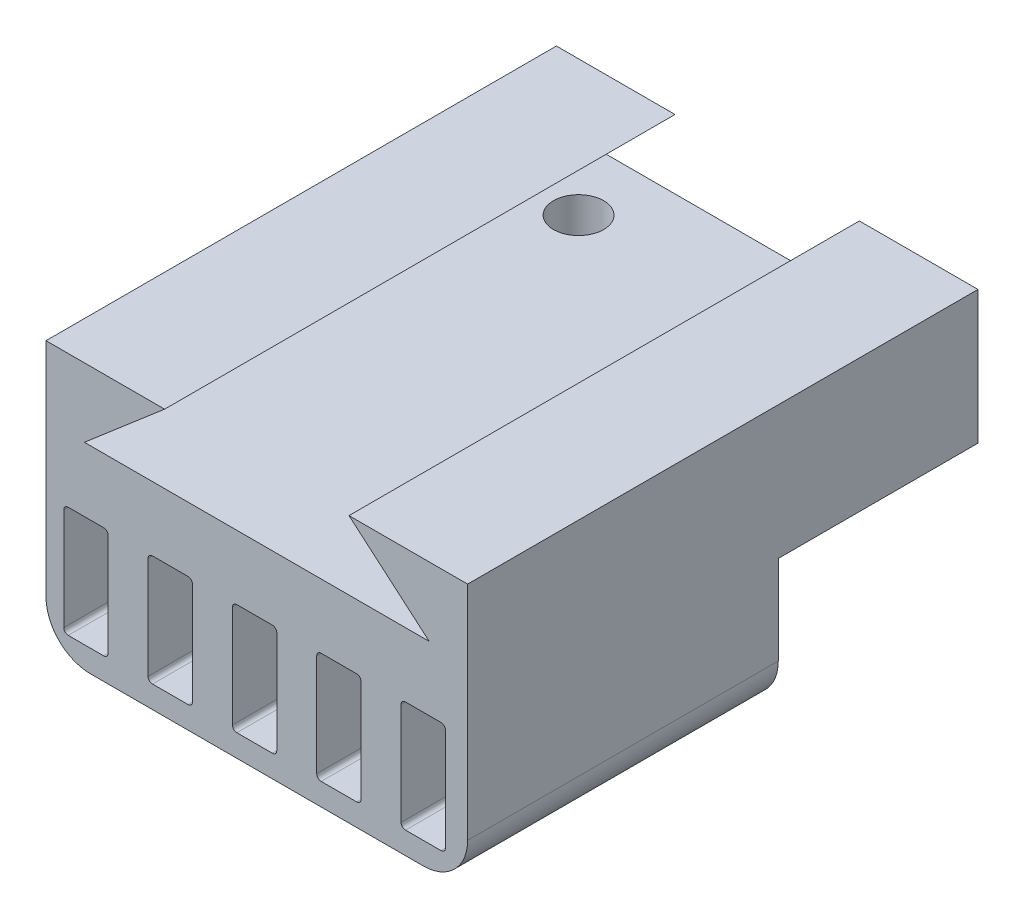
SolidWorks part; units mm, degrees
material "PLA"
ref_plane "Front" through (0, 0, 0) normal (0, 0, 1) x (1, 0, 0)
ref_plane "Top" through (0, 0, 0) normal (0, 1, 0) x (1, 0, 0)
ref_plane "Right" through (0, 0, 0) normal (1, 0, 0) x (0, 0, -1)
sketch "Sketch1" plane through (0, 0, 0) normal (0, 0, 1) x (1, 0, 0)
  line L0 (5.08, -21.59) -> (-5.08, -21.59)
  line L5 (-5.1627, -21.4936) -> (5.1627, -21.4936)
  line L6 (-5.1627, -21.4936) -> (-9.8683, -25.527)
  line L7 (-9.8683, -25.527) -> (9.8683, -25.527)
  line L8 (9.8683, -25.527) -> (5.1627, -21.4936)
  line L9 (-5.08, -21.59) -> (-5.2751, -21.59)
  line L10 (5.08, -21.59) -> (5.2751, -21.59)
  line L11 (-5.08, -21.59) -> (-5.2751, -21.59)
  line L12 (9.525, -21.59) -> (9.525, -17.6598)
  line L13 (5.08, -21.59) -> (9.525, -21.59)
  line L14 (9.525, -25.4) -> (5.08, -21.59)
  line L15 (-9.525, -25.4) -> (9.525, -25.4)
  line L16 (-5.08, -21.59) -> (-9.525, -25.4)
  line L17 (-9.525, -21.59) -> (-5.08, -21.59)
  line L18 (-9.525, -17.6598) -> (-9.525, -21.59)
  line L19 (9.525, -21.59) -> (9.525, -17.6598)
  line L20 (5.08, -21.59) -> (9.525, -21.59)
  line L21 (9.525, -25.4) -> (5.08, -21.59)
  line L22 (-9.525, -25.4) -> (9.525, -25.4)
  line L23 (-5.08, -21.59) -> (-9.525, -25.4)
  line L24 (-9.525, -21.59) -> (-5.08, -21.59)
  line L25 (-9.525, -17.6598) -> (-9.525, -21.59)
  line L27 (-12.065, -29.21) -> (12.065, -29.21)
  line L28 (-12.065, -29.21) -> (-12.065, -21.59)
  line L29 (-12.065, -21.59) -> (12.065, -21.59)
  line L30 (12.065, -29.21) -> (12.065, -21.59)
  arc A2 (-20.6375, -11.1054) -> (-19.2555, -10.6965) centre (-20.6375, -8.5654) ccw
  arc A3 (19.2555, -10.6965) -> (20.6375, -11.1054) centre (20.6375, -8.5654) ccw
  arc A4 (-20.6375, -11.1054) -> (-19.2555, -10.6965) centre (-20.6375, -8.5654) ccw
  arc A5 (19.2555, -10.6965) -> (20.6375, -11.1054) centre (20.6375, -8.5654) ccw
  ellipse E2 centre (0, 0) end of major axis (25.4, 0) minor radius 19.05 (-20.6375, -11.1054) -> (-9.525, -17.6598) ccw
  ellipse E3 centre (0, 0) end of major axis (25.4, 0) minor radius 19.05 (9.525, -17.6598) -> (20.6375, -11.1054) ccw
  ellipse E4 centre (0, 0) end of major axis (25.4, 0) minor radius 19.05 (-20.6375, -11.1054) -> (-9.525, -17.6598) ccw
  ellipse E5 centre (0, 0) end of major axis (25.4, 0) minor radius 19.05 (9.525, -17.6598) -> (20.6375, -11.1054) ccw
  spline S1 degree 3 poles (-2166.445, -15849.0793) (-418.6607, -134.144) (57.4604, 23.5329) (18.4102, -11.4784) (18.1685, -11.6861) (17.4022, -12.3125) (16.8339, -12.7373) (15.8949, -13.3659) (15.5674, -13.5742) (14.8823, -13.9857) (14.5239, -14.1894) (13.7828, -14.586) (13.3995, -14.7793) (12.6066, -15.1542) (12.1964, -15.336) (11.3542, -15.6842) (10.9219, -15.8506) (10.0343, -16.1671) (9.5775, -16.3175) (8.1859, -16.7374) (7.2281, -16.9768) (5.7448, -17.2706) (5.2427, -17.3576) (4.2222, -17.5087) (3.7022, -17.5728) (2.6581, -17.6756) (2.1332, -17.7144) (1.0777, -17.7665) (0.5456, -17.7797) (-1.0381, -17.7806) (-2.0822, -17.7301) (-3.6313, -17.5808) (-4.1449, -17.5187) (-5.1662, -17.3701) (-5.6756, -17.2832) (-6.6756, -17.0872) (-7.1675, -16.9781) (-8.1355, -16.7387) (-8.6125, -16.608) (-9.5437, -16.3283) (-9.9984, -16.1792) (-10.887, -15.8637) (-11.3215, -15.697) (-12.5878, -15.1754) (-13.3817, -14.7994) (-14.8691, -14.0059) (-15.5563, -13.5917) (-16.8227, -12.7456) (-17.3958, -12.3175) (-61.9722, 24.1081) (359.4859, -21.3348) (4215.4566, -15431.1683) knots -5.38 -5.38 -5.38 -5.38 0.03125 0.03125 0.0625 0.0625 0.125 0.125 0.15625 0.15625 0.1875 0.1875 0.21875 0.21875 0.25 0.25 0.28125 0.28125 0.3125 0.3125 0.375 0.375 0.40625 0.40625 0.4375 0.4375 0.46875 0.46875 0.5 0.5 0.5625 0.5625 0.59375 0.59375 0.625 0.625 0.65625 0.65625 0.6875 0.6875 0.71875 0.71875 0.75 0.75 0.8125 0.8125 0.875 0.875 0.9375 0.9375 6.300617 6.300617 6.300617 6.300617 only from (19.2555, -10.6965) to (-19.2555, -10.6965)
  spline S2 degree 3 poles (19.2555, -10.6965) (19.0657, -10.8817) (18.8587, -11.0763) (18.4102, -11.4784) (18.1685, -11.6861) (17.4022, -12.3125) (16.8339, -12.7373) (15.8949, -13.3659) (15.5674, -13.5742) (14.8823, -13.9857) (14.5239, -14.1894) (13.7828, -14.586) (13.3995, -14.7793) (12.6066, -15.1542) (12.1964, -15.336) (11.3542, -15.6842) (10.9219, -15.8506) (10.0343, -16.1671) (9.5775, -16.3175) (8.1859, -16.7374) (7.2281, -16.9768) (5.7448, -17.2706) (5.2427, -17.3576) (4.2222, -17.5087) (3.7022, -17.5728) (2.6581, -17.6756) (2.1332, -17.7144) (1.0777, -17.7665) (0.5456, -17.7797) (-1.0381, -17.7806) (-2.0822, -17.7301) (-3.6313, -17.5808) (-4.1449, -17.5187) (-5.1662, -17.3701) (-5.6756, -17.2832) (-6.6756, -17.0872) (-7.1675, -16.9781) (-8.1355, -16.7387) (-8.6125, -16.608) (-9.5437, -16.3283) (-9.9984, -16.1792) (-10.887, -15.8637) (-11.3215, -15.697) (-12.5878, -15.1754) (-13.3817, -14.7994) (-14.8691, -14.0059) (-15.5563, -13.5917) (-16.8227, -12.7456) (-17.3958, -12.3175) (-18.4228, -11.4783) (-18.8731, -11.0698) (-19.2555, -10.6965) knots 0 0 0 0 0.03125 0.03125 0.0625 0.0625 0.125 0.125 0.15625 0.15625 0.1875 0.1875 0.21875 0.21875 0.25 0.25 0.28125 0.28125 0.3125 0.3125 0.375 0.375 0.40625 0.40625 0.4375 0.4375 0.46875 0.46875 0.5 0.5 0.5625 0.5625 0.59375 0.59375 0.625 0.625 0.65625 0.65625 0.6875 0.6875 0.71875 0.71875 0.75 0.75 0.8125 0.8125 0.875 0.875 0.9375 0.9375 1 1 1 1
  dimension "D1" = 0
  dimension "D2" = 2.54
  dimension "D3" = 2.54
  dimension "D4" = 7.62
  dimension "D5" = 0.127
extrude "Boss-Extrude2" add sketch "Sketch1" along normal blind 25.4 contours L27 L30 L29 L20 L8 L7 L6 L24 L28
sketch "Sketch3" plane through (0, -29.21, 0) normal (0, -1, 0) x (-1, 0, 0)
  line L0 (12.065, -25.4) -> (12.065, 0) construction
  line L1 (-12.065, -25.4) -> (12.065, -25.4)
  line L2 (-12.065, -25.4) -> (-12.065, -7.62)
  line L3 (-12.065, -7.62) -> (12.065, -7.62)
  line L4 (12.065, -25.4) -> (12.065, -7.62)
  dimension "D1" = 17.78
extrude "Boss-Extrude3" add sketch "Sketch3" along normal blind 7.62
sketch "Sketch4" plane through (0, 0, 25.4) normal (0, 0, 1) x (1, 0, 0)
  line L0 (12.065, -36.83) -> (-12.065, -36.83) construction
  line L1 (10.541, -35.56) -> (8.509, -35.56)
  line L2 (10.795, -35.306) -> (10.795, -29.464)
  line L3 (10.541, -29.21) -> (8.509, -29.21)
  line L4 (8.255, -35.306) -> (8.255, -29.464)
  line L5 (12.065, -36.83) -> (12.065, -21.59) construction
  line L6 (5.969, -35.306) -> (5.969, -29.464)
  line L7 (5.715, -35.56) -> (3.683, -35.56)
  line L8 (3.429, -35.306) -> (3.429, -29.464)
  line L9 (5.715, -29.21) -> (3.683, -29.21)
  line L10 (1.143, -35.306) -> (1.143, -29.464)
  line L11 (0.889, -35.56) -> (-1.143, -35.56)
  line L12 (-1.397, -35.306) -> (-1.397, -29.464)
  line L13 (0.889, -29.21) -> (-1.143, -29.21)
  line L14 (-3.683, -35.306) -> (-3.683, -29.464)
  line L15 (-3.937, -35.56) -> (-5.969, -35.56)
  line L16 (-6.223, -35.306) -> (-6.223, -29.464)
  line L17 (-3.937, -29.21) -> (-5.969, -29.21)
  line L18 (-8.509, -35.306) -> (-8.509, -29.464)
  line L19 (-8.763, -35.56) -> (-10.795, -35.56)
  line L20 (-11.049, -35.306) -> (-11.049, -29.464)
  line L21 (-8.763, -29.21) -> (-10.795, -29.21)
  arc A0 (8.509, -29.21) -> (8.255, -29.464) centre (8.509, -29.464) ccw
  arc A1 (10.795, -29.464) -> (10.541, -29.21) centre (10.541, -29.464) ccw
  arc A2 (8.509, -35.56) -> (8.255, -35.306) centre (8.509, -35.306) cw
  arc A3 (10.541, -35.56) -> (10.795, -35.306) centre (10.541, -35.306) ccw
  arc A4 (5.715, -35.56) -> (5.969, -35.306) centre (5.715, -35.306) ccw
  arc A5 (5.969, -29.464) -> (5.715, -29.21) centre (5.715, -29.464) ccw
  arc A6 (3.683, -35.56) -> (3.429, -35.306) centre (3.683, -35.306) cw
  arc A7 (3.683, -29.21) -> (3.429, -29.464) centre (3.683, -29.464) ccw
  arc A8 (0.889, -35.56) -> (1.143, -35.306) centre (0.889, -35.306) ccw
  arc A9 (1.143, -29.464) -> (0.889, -29.21) centre (0.889, -29.464) ccw
  arc A10 (-1.143, -35.56) -> (-1.397, -35.306) centre (-1.143, -35.306) cw
  arc A11 (-1.143, -29.21) -> (-1.397, -29.464) centre (-1.143, -29.464) ccw
  arc A12 (-3.937, -35.56) -> (-3.683, -35.306) centre (-3.937, -35.306) ccw
  arc A13 (-3.683, -29.464) -> (-3.937, -29.21) centre (-3.937, -29.464) ccw
  arc A14 (-5.969, -35.56) -> (-6.223, -35.306) centre (-5.969, -35.306) cw
  arc A15 (-5.969, -29.21) -> (-6.223, -29.464) centre (-5.969, -29.464) ccw
  arc A16 (-8.763, -35.56) -> (-8.509, -35.306) centre (-8.763, -35.306) ccw
  arc A17 (-8.509, -29.464) -> (-8.763, -29.21) centre (-8.763, -29.464) ccw
  arc A18 (-10.795, -35.56) -> (-11.049, -35.306) centre (-10.795, -35.306) cw
  arc A19 (-10.795, -29.21) -> (-11.049, -29.464) centre (-10.795, -29.464) ccw
  point P12 (10.795, -29.21)
  point P15 (8.255, -35.56)
  point P18 (10.795, -35.56)
  dimension "D5" = 0.254
  dimension "D1" = 2.54
  dimension "D2" = 6.35
  dimension "D3" = 1.27
  dimension "D4" = 1.27
  dimension "D6" = 5
extrude "Cut-Extrude2" cut sketch "Sketch4" against normal offset from surface (16.51 mm away) 1.27 up to face at (0, -33.02, 7.62)
sketch "Sketch5" plane through (0, 0, 8.89) normal (0, 0, 1) x (1, 0, 0)
  line L3 (10.541, -29.21) -> (8.509, -29.21) construction
  line L8 (10.795, -35.306) -> (10.795, -29.464) construction
  circle A0 centre (9.525, -32.385) radius 1.143
  circle A1 centre (4.699, -32.385) radius 1.143
  circle A2 centre (-0.127, -32.385) radius 1.143
  circle A3 centre (-4.953, -32.385) radius 1.143
  circle A4 centre (-9.779, -32.385) radius 1.143
  dimension "D1" = 2.286
  dimension "D2" = 3.175
  dimension "D3" = 1.27
  dimension "D4" = 5
extrude "Cut-Extrude3" cut sketch "Sketch5" against normal blind 1.27
fillet "Fillet1" radius 2.54 2 edges at (-12.065, -36.83, 16.51) (12.065, -36.83, 16.51)
sketch "Sketch6" plane through (0, 0, 0) normal (0, 0, -1) x (-1, 0, 0)
  line L8 (-12.065, -29.21) -> (12.065, -29.21)
  line L9 (12.065, -29.21) -> (12.065, -21.59)
  line L10 (12.065, -21.59) -> (5.2751, -21.59)
  line L11 (5.2751, -21.59) -> (9.8683, -25.527)
  line L12 (9.8683, -25.527) -> (-9.8683, -25.527)
  line L13 (-9.8683, -25.527) -> (-5.2751, -21.59)
  line L14 (-5.2751, -21.59) -> (-12.065, -21.59)
  line L15 (-12.065, -21.59) -> (-12.065, -29.21)
  line L16 (-12.065, -29.21) -> (12.065, -29.21)
  line L17 (12.065, -29.21) -> (12.065, -21.59)
  line L18 (12.065, -21.59) -> (5.2751, -21.59)
  line L19 (5.2751, -21.59) -> (9.8683, -25.527)
  line L20 (9.8683, -25.527) -> (-9.8683, -25.527)
  line L21 (-9.8683, -25.527) -> (-5.2751, -21.59)
  line L22 (-5.2751, -21.59) -> (-12.065, -21.59)
  line L23 (-12.065, -21.59) -> (-12.065, -29.21)
  dimension "D1" = 0
extrude "Boss-Extrude4" add sketch "Sketch6" along normal blind 3.81
sketch "Sketch2" plane through (0, -29.21, 0) normal (0, -1, 0) x (-1, 0, 0)
  line L1 (-12.065, 3.81) -> (12.065, 3.81) construction
  line L2 (-12.065, -7.62) -> (-12.065, 3.81) construction
  line L3 (12.065, -7.62) -> (12.065, 3.81) construction
  circle A0 centre (-6.985, 0) radius 1.4351
  circle A1 centre (6.985, 0) radius 1.4351
  dimension "D1" = 2.8702
  dimension "D3" = 5.08
  dimension "D5" = 5.08
  dimension "D2" = 3.81
  dimension "D4" = 3.81
extrude "Cut-Extrude1" cut sketch "Sketch2" against normal up to surface (3.683 mm away) up to face at (0, -25.527, 10.795)
